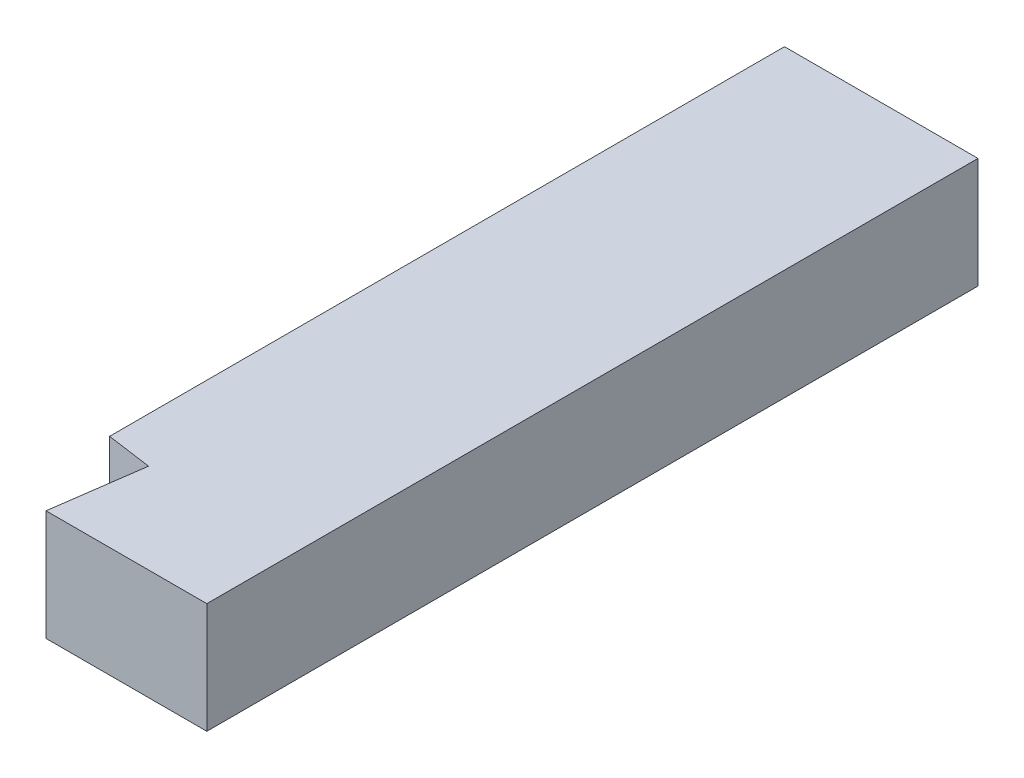
SolidWorks part; units mm, degrees
material "Pine"
ref_plane "X-Y Datum" through (0, 0, 0) normal (0, 0, 1) x (1, 0, 0)
ref_plane "X-Z Datum" through (0, 0, 0) normal (0, 1, 0) x (1, 0, 0)
ref_plane "Y-Z Datum" through (0, 0, 0) normal (1, 0, 0) x (0, 0, -1)
sketch "Sketch1" plane through (0, 0, 0) normal (0, 0, 1) x (1, 0, 0)
  line L1 (-50.8, 25.4) -> (50.8, 25.4)
  line L2 (-50.8, 25.4) -> (-50.8, -25.4)
  line L3 (-50.8, -25.4) -> (50.8, -25.4)
  line L4 (50.8, 25.4) -> (50.8, -25.4)
  line L5 (-50.8, 25.4) -> (50.8, -25.4) construction
  line L6 (-50.8, -25.4) -> (50.8, 25.4) construction
  point P0 (0, 0)
  dimension "D1" = 101.6
  dimension "D2" = 50.8
extrude "Boss-Extrude1" add sketch "Sketch1" along normal blind 354.29
sketch "Sketch2" plane through (0, 25.4, 0) normal (0, 1, 0) x (1, 0, 0)
  line L0 (-50.8, -322.8853) -> (-50.8, -310.0604)
  line L1 (-50.8, -322.8853) -> (-31.75, -325.5626) construction
  line L3 (-50.8, -354.29) -> (-50.8, 0) construction
  line L4 (-29.9825, -312.9862) -> (-50.8, -310.0604)
  line L5 (-31.75, -325.5626) -> (-29.9825, -312.9862)
  line L7 (-31.75, -325.5626) -> (-35.7874, -354.29)
  line L8 (-50.8, -354.29) -> (-50.8, 0) construction
  line L9 (-50.8, -354.29) -> (50.8, -354.29) construction
  line L10 (-50.8, -322.8853) -> (-50.8, -354.29)
  line L11 (-50.8, -354.29) -> (-35.7874, -354.29)
  point P0 (-50.8, -311.3033)
  point P4 (-49.6413, -321.8902)
  dimension "D2" = 12.7
  dimension "D1" = 98
  dimension "D5" = 28.7274
  dimension "D6" = 19.05
extrude "Cut-Extrude1" cut sketch "Sketch2" against normal through all both and the other way through all
sketch "Sketch3" plane through (0, 25.4, 0) normal (0, 1, 0) x (1, 0, 0)
  line L0 (50.8, 0) -> (-50.8, 0) construction
  line L1 (50.8, -354.29) -> (38.1, -354.29)
  line L2 (50.8, -354.29) -> (50.8, 0)
  line L3 (50.8, 0) -> (38.1, 0)
  line L4 (38.1, -354.29) -> (38.1, 0)
  line L5 (-50.8, -310.0604) -> (-50.8, 0) construction
  dimension "D1" = 88.9
extrude "Cut-Extrude2" cut sketch "Sketch3" against normal through all both
